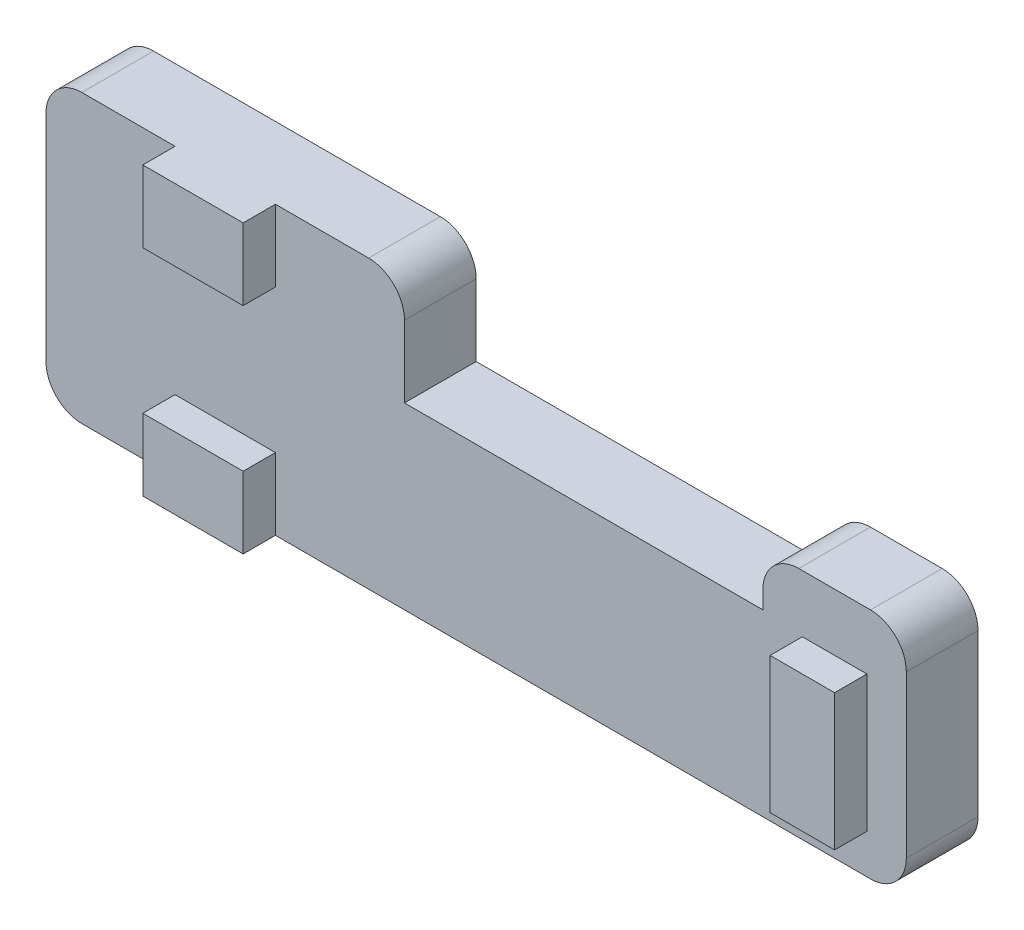
SolidWorks part; units mm, degrees
ref_plane "Front Plane" through (0, 0, 0) normal (0, 0, 1) x (1, 0, 0)
ref_plane "Top Plane" through (0, 0, 0) normal (0, 1, 0) x (1, 0, 0)
ref_plane "Right Plane" through (0, 0, 0) normal (1, 0, 0) x (0, 0, -1)
sketch "Sketch1" plane through (0, 0, 0) normal (0, 1, 0) x (1, 0, 0)
  line L1 (0, 0) -> (10, 0)
  line L2 (0, 0) -> (0, 18)
  line L3 (0, 18) -> (10, 18)
  line L4 (10, 0) -> (10, 18)
  dimension "D1" = 18
  dimension "D2" = 10
extrude "Extrude-Thin1" add sketch "Sketch1" along normal blind 2 thin
sketch "Sketch2" plane through (0, 2, 0) normal (0, 1, 0) x (1, 0, 0)
  line L0 (-2, -2) -> (12, -2) construction
  line L1 (12, 20) -> (10, 20)
  line L2 (12, 20) -> (12, -2)
  line L3 (12, -2) -> (10, -2)
  line L4 (10, 20) -> (10, -2)
extrude "Boss-Extrude1" add sketch "Sketch2" along normal blind 4.5
sketch "Sketch3" plane through (-2, 0, 0) normal (-1, 0, 0) x (0, 0, 1)
  line L6 (-20, 0) -> (2, 0)
  line L7 (-20, 0) -> (-20, 8)
  line L8 (-20, 8) -> (2, 8)
  line L9 (2, 0) -> (2, 8)
  dimension "D1" = 8
extrude "Extrude-Thin2" add sketch "Sketch3" against normal blind 2 thin thin type one direction reverse wall 2
sketch "Sketch4" plane through (12, 0, 0) normal (1, 0, 0) x (0, 0, -1)
  line L0 (-2, 8) -> (20, 8) construction
  line L1 (18, 8) -> (-2, 8)
  line L2 (18, 8) -> (18, 0)
  line L3 (18, 0) -> (-2, 0)
  line L4 (-2, 8) -> (-2, 0)
  line L5 (-2, 6.5) -> (-2, 0) construction
  line L6 (20, 6.5) -> (20, 0) construction
  dimension "D1" = 2
extrude "Cut-Extrude1" cut sketch "Sketch4" against normal blind 26 contours L2 L1 L4 L3
sketch "Sketch5" plane through (0, 0, -18) normal (0, 0, 1) x (1, 0, 0)
  line L0 (10, 3) -> (12, 3) construction
  line L1 (-2, 8) -> (-1.1, 8)
  line L2 (-2, 8) -> (-2, 6.1)
  line L3 (-2, 6.1) -> (-1.1, 6.1)
  line L4 (-1.1, 8) -> (-1.1, 6.1)
  line L5 (-2, 0) -> (-1.1, 0)
  line L6 (-2, 0) -> (-2, 1.9)
  line L7 (-2, 1.9) -> (-1.1, 1.9)
  line L8 (-1.1, 0) -> (-1.1, 1.9)
  line L9 (10, 2) -> (10, 6.5) construction
  line L10 (12, 6.5) -> (12, 0) construction
  line L11 (12, 0) -> (-2, 0) construction
  line L12 (12, 4.9) -> (12, 1.1)
  line L13 (12.9, 1.1) -> (11.1, 1.1)
  line L14 (12.9, 1.1) -> (12.9, 4.9)
  line L15 (12.9, 4.9) -> (11.1, 4.9)
  line L16 (11.1, 1.1) -> (11.1, 4.9)
  line L17 (12.9, 1.1) -> (11.1, 4.9) construction
  line L18 (12.9, 4.9) -> (11.1, 1.1) construction
  line M14 (-2, 0) -> (12, 0)
  line M15 (12, 0) -> (12, 6.5)
  line M20 (0, 8) -> (-2, 8)
  line M21 (-2, 8) -> (-2, 0)
  dimension "D1" = 0.9
  dimension "D2" = 1.9
  dimension "D3" = 1.9
  dimension "D4" = 0.9
  dimension "D5" = 3
  dimension "D6" = 3.8
  dimension "D7" = 1.8
extrude "Boss-Extrude2" add sketch "Sketch5" along normal blind 0.9 contours L4 L3 M20 M21 | L8 L7 M14 M21 | L16 L13 L15 M15
sketch "Sketch6" plane through (-2, 0, 0) normal (-1, 0, 0) x (0, 0, 1)
  line L0 (-18, 6.1) -> (-18, 8)
  line L1 (-18, 1.9) -> (-20, 1.9)
  line L2 (-18, 1.9) -> (-18, 0)
  line L3 (-18, 0) -> (-20, 0)
  line L4 (-20, 1.9) -> (-20, 0)
  line L12 (-18, 1.9) -> (-18, 6.1)
  line L13 (-18, 6.1) -> (-17.1, 6.1)
  line L14 (-17.1, 6.1) -> (-17.1, 8)
  line L15 (-17.1, 8) -> (-20, 8)
  line L16 (-20, 8) -> (-20, 0)
  line L17 (-20, 0) -> (-17.1, 0)
  line L18 (-17.1, 0) -> (-17.1, 1.9)
  line L19 (-17.1, 1.9) -> (-18, 1.9)
  line L20 (-18, 1.9) -> (-18, 6.1)
  line L21 (-18, 6.1) -> (-17.1, 6.1)
  line L22 (-17.1, 6.1) -> (-17.1, 8)
  line L23 (-17.1, 8) -> (-20, 8)
  line L24 (-20, 8) -> (-20, 0)
  line L25 (-20, 0) -> (-17.1, 0)
  line L26 (-17.1, 0) -> (-17.1, 1.9)
  line L27 (-17.1, 1.9) -> (-18, 1.9)
  line M13 (-18, 1.9) -> (-18, 6.1)
  line M16 (-17.1, 8) -> (-20, 8)
  line M17 (-20, 8) -> (-20, 0)
  line M18 (-20, 0) -> (-17.1, 0)
  dimension "D1" = 0
extrude "Boss-Extrude3" add sketch "Sketch6" along normal blind 8 contours L1 L0 M13 M16 M17 | L2 L1 M17 M18
sketch "Sketch7" plane through (0, 0, -18) normal (0, 0, 1) x (1, 0, 0)
  line L0 (-10, 8) -> (-2, 8) construction
  line L1 (-3.6, 8) -> (-6.4, 8)
  line L2 (-3.6, 8) -> (-3.6, 6)
  line L3 (-3.6, 6) -> (-6.4, 6)
  line L4 (-6.4, 8) -> (-6.4, 6)
  line L5 (0, 8) -> (0, 2) construction
  line L6 (-10, 4) -> (0, 4) construction
  line L7 (-10, 0) -> (-10, 8) construction
  line L8 (-3.6, 0) -> (-3.6, 2)
  line L9 (-3.6, 0) -> (-6.4, 0)
  line L10 (-6.4, 0) -> (-6.4, 2)
  line L11 (-3.6, 2) -> (-6.4, 2)
  dimension "D1" = 3.6
  dimension "D2" = 3.6
extrude "Boss-Extrude4" add sketch "Sketch7" along normal blind 0.9
sketch "Sketch8" plane through (0, 8, 0) normal (0, 1, 0) x (1, 0, 0)
  line L1 (-2, 18) -> (-1.1, 18)
  line L2 (-2, 18) -> (-2, 17.1)
  line L3 (-2, 17.1) -> (-1.1, 17.1)
  line L4 (-1.1, 18) -> (-1.1, 17.1)
extrude "Cut-Extrude2" cut sketch "Sketch8" against normal through all
sketch "Sketch9" plane through (0, 0, 0) normal (1, 0, 0) x (0, 0, -1)
  line L1 (18, 2) -> (20, 2)
  line L2 (18, 2) -> (18, 5)
  line L3 (18, 5) -> (20, 5)
  line L4 (20, 8) -> (18, 8)
  line L5 (18, 8) -> (18, 2)
  line L6 (18, 2) -> (20, 2)
  line L7 (20, 2) -> (20, 8)
  line L8 (20, 8) -> (18, 8)
  line L9 (18, 8) -> (18, 2)
  line L10 (18, 2) -> (20, 2)
  line L11 (20, 2) -> (20, 8)
  line L12 (20, 2) -> (20, 5)
  line M8 (18, 8) -> (18, 2)
  line M9 (18, 2) -> (20, 2)
  line M10 (20, 2) -> (20, 8)
  dimension "D2" = 3
  dimension "D1" = 0
extrude "Boss-Extrude5" add sketch "Sketch9" along normal through all contours L3 M8 M9 M10
sketch "Sketch10" plane through (12, 0, 0) normal (1, 0, 0) x (0, 0, -1)
  line L8 (18, 6.5) -> (18, 4.9)
  line L9 (18, 4.9) -> (17.1, 4.9)
  line L10 (17.1, 4.9) -> (17.1, 1.1)
  line L11 (17.1, 1.1) -> (18, 1.1)
  line L12 (18, 1.1) -> (18, 0)
  line L13 (18, 0) -> (20, 0)
  line L14 (20, 0) -> (20, 6.5)
  line L15 (20, 6.5) -> (18, 6.5)
  line L16 (18, 6.5) -> (18, 4.9)
  line L17 (18, 4.9) -> (17.1, 4.9)
  line L18 (17.1, 4.9) -> (17.1, 1.1)
  line L19 (17.1, 1.1) -> (18, 1.1)
  line L20 (18, 1.1) -> (18, 0)
  line L21 (18, 0) -> (20, 0)
  line L22 (20, 0) -> (20, 6.5)
  line L23 (20, 6.5) -> (18, 6.5)
  dimension "D1" = 0
extrude "Boss-Extrude6" add sketch "Sketch10" along normal blind 2
sketch "Sketch11" plane through (0, 0, -18) normal (0, 0, 1) x (1, 0, 0)
  line L6 (10, 5) -> (10, 6.5) construction
  line L7 (11.1, 1.1) -> (10, 1.1)
  line L8 (11.1, 1.1) -> (11.1, 4.9)
  line L9 (11.1, 4.9) -> (10, 4.9)
  line L10 (10, 1.1) -> (10, 4.9)
  line L11 (14, 4.9) -> (11.1, 4.9) construction
  dimension "D1" = 0
  dimension "D2" = 0
extrude "Boss-Extrude7" add sketch "Sketch11" along normal blind 0.9
sketch "Sketch12" plane through (0, 0, -17.1) normal (0, 0, 1) x (1, 0, 0)
  line L0 (10, 3) -> (14, 3) construction
  line L1 (10, 4.9) -> (10, 1.1) construction
  line L2 (14, 4.9) -> (14, 1.1) construction
  line L3 (14, 4.9) -> (10, 4.9) construction
  line L4 (11.1, 1.1) -> (12.9, 1.1)
  line L5 (11.1, 1.1) -> (11.1, 4.9)
  line L6 (11.1, 4.9) -> (12.9, 4.9)
  line L7 (12.9, 1.1) -> (12.9, 4.9)
  line L8 (11.1, 1.1) -> (12.9, 4.9) construction
  line L9 (11.1, 4.9) -> (12.9, 1.1) construction
  line L11 (10, 4.9) -> (14, 4.9)
  line L12 (10, 4.9) -> (10, 1.1)
  line L13 (10, 1.1) -> (14, 1.1)
  line L14 (14, 4.9) -> (14, 1.1)
  point P6 (12, 3)
  line M5 (14, 4.9) -> (10, 4.9)
  line M6 (10, 4.9) -> (10, 1.1)
  line M7 (10, 1.1) -> (14, 1.1)
  line M8 (14, 1.1) -> (14, 4.9)
  dimension "D1" = 1.8
extrude "Cut-Extrude3" cut sketch "Sketch12" against normal blind 0.9 contours L5 M7 M5 M6 | L7 M7 M8 M5
fillet "Fillet1" radius 1 6 edges at (-10, 0, -19) (-10, 8, -19) (14, 0, -19) (14, 6.5, -19) (10, 6.5, -19) (0, 8, -19)
